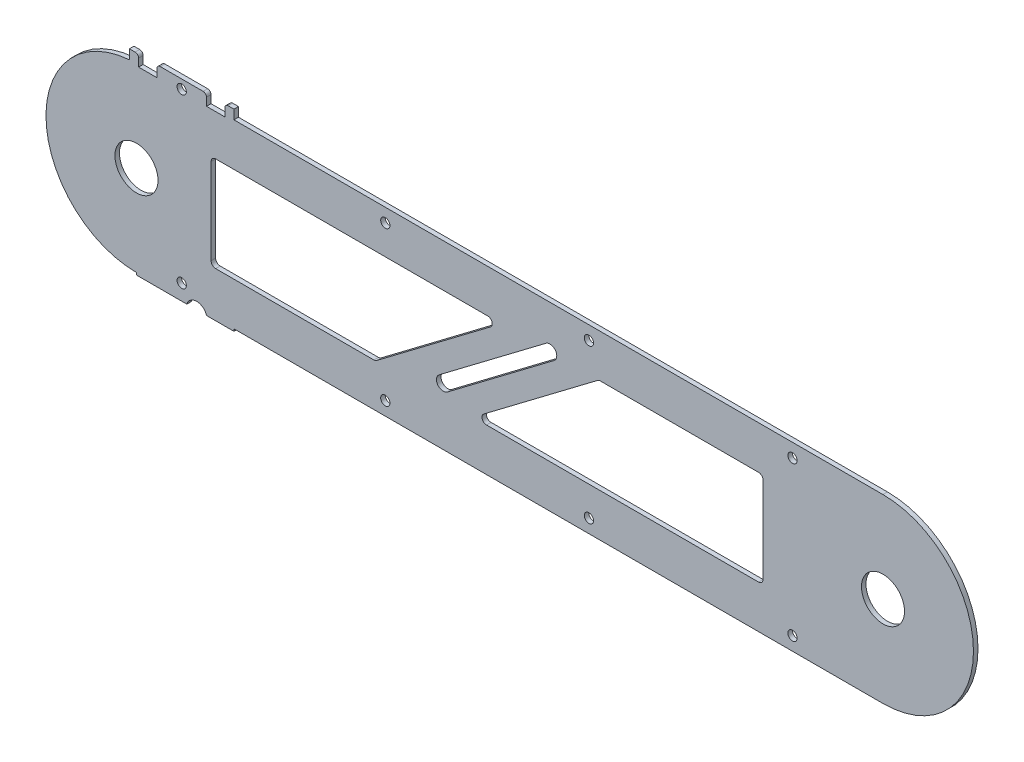
SolidWorks part; units mm, degrees
ref_plane "前视基准面" through (0, 0, 0) normal (0, 0, 1) x (1, 0, 0)
ref_plane "上视基准面" through (0, 0, 0) normal (0, 1, 0) x (1, 0, 0)
ref_plane "右视基准面" through (0, 0, 0) normal (1, 0, 0) x (0, 0, -1)
sketch "草图1" plane through (0, 0, 0) normal (0, 0, 1) x (1, 0, 0)
  line L0 (328.5429, -0.1457) -> (-1.4571, -0.1457) construction
  line L8 (328.5429, -40.1457) -> (-1.4571, -40.1457)
  line L9 (-1.4571, 39.8543) -> (328.5429, 39.8543)
  circle A0 centre (-1.4571, -0.1457) radius 9.52
  circle A1 centre (-1.4571, -0.1457) radius 40 construction
  arc A4 (-1.4571, 39.8543) -> (-1.4571, -40.1457) centre (-1.4571, -0.1457) ccw
  circle A11 centre (328.5429, -0.1457) radius 9.52
  circle A12 centre (328.5429, -0.1457) radius 40 construction
  circle A16 centre (328.5429, -0.1457) radius 30 construction
  arc A20 (328.5429, 39.8543) -> (328.5429, -40.1457) centre (328.5429, -0.1457) cw
  dimension "D1" = 330
  dimension "D2" = 19.04
  dimension "D4" = 19.04
  dimension "D5" = 80
extrude "凸台-拉伸1" add sketch "草图1" along normal blind 2
sketch "草图4" plane through (0, 0, 2) normal (0, 0, 1) x (1, 0, 0)
  line L0 (-1.4571, -40.1457) -> (-1.4571, -41.1257)
  line L1 (328.5429, 39.8543) -> (-1.4571, 39.8543) construction
  line L2 (41.6429, 35.3514) -> (-4.5571, 35.3514)
  line L3 (41.6429, 35.3514) -> (41.6429, 43.9543)
  line L4 (41.6429, 43.9543) -> (-4.5571, 43.9543)
  line L5 (-4.5571, 35.3514) -> (-4.5571, 43.9543)
  line L6 (-1.4571, -41.1257) -> (41.6429, -41.1257)
  line L7 (41.6429, -41.1257) -> (41.6429, -40.1457)
  line L8 (-1.4571, -40.1457) -> (328.5429, -40.1457) construction
  line L9 (41.6429, -40.1457) -> (-1.4571, -40.1457)
  dimension "D1" = 46.2
  dimension "D2" = 3.1
  dimension "D3" = 4.1
  dimension "D4" = 0.98
extrude "凸台-拉伸2" add sketch "草图4" against normal blind 2
sketch "草图2" plane through (0, 0, 2) normal (0, 0, 1) x (1, 0, 0)
  line L0 (198.5429, 33.8543) -> (288.5429, 33.8543) construction
  line L1 (18.5429, 33.8543) -> (198.5429, 33.8543) construction
  line L2 (108.5429, -34.1457) -> (198.5429, 33.8543) construction
  line L3 (18.5429, 33.8543) -> (18.5429, -34.1457) construction
  line L4 (18.5429, -34.1457) -> (108.5429, -34.1457) construction
  line L5 (31.5429, -21.1457) -> (104.1839, -21.1457)
  line L6 (104.1839, -21.1457) -> (159.7721, 20.8543)
  line L7 (31.5429, 20.8543) -> (159.7721, 20.8543)
  line L8 (31.5429, 20.8543) -> (31.5429, -21.1457)
  line L9 (108.5429, -34.1457) -> (288.5429, -34.1457) construction
  line L10 (288.5429, -34.1457) -> (288.5429, 33.8543) construction
  line L12 (275.5429, 20.8543) -> (202.9018, 20.8543)
  line L13 (147.3136, -21.1457) -> (202.9018, 20.8543)
  line L14 (147.3136, -21.1457) -> (275.5429, -21.1457)
  line L15 (275.5429, -21.1457) -> (275.5429, 20.8543)
  line L20 (18.5429, 33.8543) -> (18.5429, 39.8543) construction
  line L28 (288.5429, 33.8543) -> (198.5429, 33.8543) construction
  line L30 (328.5429, 39.8543) -> (41.6429, 39.8543) construction
  line L31 (7.5929, 38.9643) -> (-0.5071, 41.0643) construction
  line L36 (29.4929, 41.0643) -> (37.5929, 41.0643) construction
  line L37 (29.4929, 41.0643) -> (29.4929, 38.9643)
  line L38 (29.4929, 38.9643) -> (37.5929, 38.9643)
  line L39 (37.5929, 41.0643) -> (37.5929, 38.9643)
  line L40 (29.4929, 41.0643) -> (37.5929, 38.9643) construction
  line L41 (29.4929, 38.9643) -> (37.5929, 41.0643) construction
  line L42 (7.5929, 41.0643) -> (-0.5071, 38.9643) construction
  line L43 (18.5429, 33.8543) -> (-161.4571, 33.8543) construction
  line L44 (-0.5071, 41.0643) -> (-0.5071, 38.9643)
  line L45 (7.5929, 38.9643) -> (-0.5071, 38.9643)
  line L46 (7.5929, 41.0643) -> (7.5929, 38.9643)
  line L47 (7.5929, 41.0643) -> (-0.5071, 41.0643) construction
  line L48 (-0.5071, 41.0643) -> (-0.5071, 53.5797)
  line L49 (-0.5071, 53.5797) -> (7.5929, 53.5797)
  line L50 (7.5929, 53.5797) -> (7.5929, 41.0643)
  line L51 (29.4929, 41.0643) -> (29.4929, 53.5797)
  line L52 (29.4929, 53.5797) -> (37.5929, 53.5797)
  line L53 (37.5929, 53.5797) -> (37.5929, 41.0643)
  circle A1 centre (108.5429, 33.8543) radius 2.05
  circle A2 centre (198.5429, 33.8543) radius 2.05
  circle A3 centre (288.5429, 33.8543) radius 2.05
  circle A4 centre (108.5429, -34.1457) radius 2.05
  circle A5 centre (198.5429, -34.1457) radius 2.05
  circle A6 centre (288.5429, -34.1457) radius 2.05
  circle A7 centre (18.5429, -34.1457) radius 2.05
  circle A9 centre (18.5429, 40.0143) radius 2.05
  point P0 (3.5429, 40.0143)
  point P2 (-1.4571, -0.1457)
  point P30 (33.5429, 40.0143)
  dimension "D1" = 8.1
  dimension "D2" = 34
  dimension "D3" = 2.1
  dimension "D8" = 6.16
  dimension "D4" = 15
  dimension "D6" = 13
  dimension "D7" = 13
extrude "切除-拉伸1" cut sketch "草图2" against normal blind 4
sketch "草图3" plane through (0, 0, 2) normal (0, 0, 1) x (1, 0, 0)
  line L0 (202.9018, 20.8543) -> (159.7721, 20.8543) construction
  line L1 (147.3136, -21.1457) -> (104.1839, -21.1457) construction
  line L2 (181.337, 20.8543) -> (125.7487, -21.1457) construction
  line L3 (181.337, 20.8543) -> (134.1674, -14.785) construction
  line L4 (183.1455, 18.4607) -> (135.9759, -17.1786)
  line L5 (179.5285, 23.2479) -> (132.3589, -12.3914)
  arc A0 (183.1455, 18.4607) -> (179.5285, 23.2479) centre (181.337, 20.8543) ccw
  arc A1 (132.3589, -12.3914) -> (135.9759, -17.1786) centre (134.1674, -14.785) ccw
  point P11 (157.7522, 3.0347)
extrude "切除-拉伸2" cut sketch "草图3" against normal blind 10
fillet "圆角1" radius 2 8 edges at (275.5429, -21.1457, 1) (275.5429, 20.8543, 1) (202.9018, 20.8543, 1) (147.3136, -21.1457, 1) (104.1839, -21.1457, 1) (159.7721, 20.8543, 1) (31.5429, -21.1457, 1) (31.5429, 20.8543, 1)
sketch "草图5" plane through (0, 0, 2) normal (0, 0, 1) x (1, 0, 0)
  line L0 (-1.4571, -41.1257) -> (41.6429, -41.1257) construction
  line L1 (20.8062, -41.1257) -> (29.5079, -41.1257)
  arc A0 (20.8062, -41.1257) -> (29.5079, -41.1257) centre (25.157, -42.4207) cw
  point P3 (29.5079, -41.1257)
  point P6 (20.8062, -41.1257)
extrude "切除-拉伸3" cut sketch "草图5" against normal blind 2
fillet "圆角2" radius 1.5 4 edges at (37.5929, 43.9543, 1) (29.4929, 43.9543, 1) (7.5929, 43.9543, 1) (-0.5071, 43.9543, 1)
